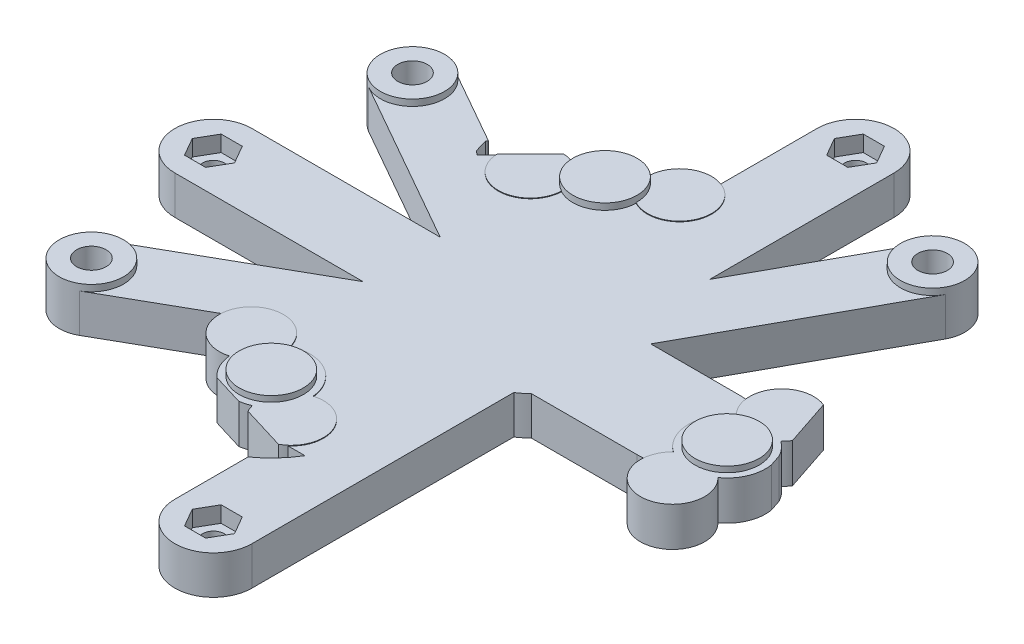
SolidWorks part; units mm, degrees
other "Fixed Star Plate"
ref_plane "Front Plane" through (0, 0, 0) normal (0, 0, 1) x (1, 0, 0)
ref_plane "Top Plane" through (0, 0, 0) normal (0, 1, 0) x (1, 0, 0)
ref_plane "Right Plane" through (0, 0, 0) normal (1, 0, 0) x (0, 0, -1)
sketch3d "Base Outline Sketch datum points"
  point P0 (0, -71, 0)
  point P1 (10, -71, 0)
  point P2 (0, -71, -10)
ref_plane "Base Outline Sketch plane" through (0, -71, 0) normal (0, 1, 0) x (1, 0, 0)
sketch "Base Outline Sketch" plane through (0, -71, 0) normal (0, 1, 0) x (1, 0, 0)
  line L0 (-32.2917, 8) -> (-46.1853, 8)
  line L1 (-24.4227, 13.1376) -> (-22.0154, 5.909)
  line L2 (-20.9711, 2.7735) -> (-20.3706, 0.9703)
  line L3 (-48.7418, -8) -> (-32.2917, -8)
  line L4 (-50.2917, -50) -> (-50.2917, -9.2195)
  line L5 (-62.2917, -38.6002) -> (-62.2917, -50)
  line L6 (-58.0273, -34) -> (-60.6452, -34)
  line L7 (-61.5389, -34.6217) -> (-68.3642, -32.542)
  line L8 (-70.4166, -31.9166) -> (-75.3281, -30.42)
  line L9 (-97.8216, -29.3473) -> (-83.633, -21.2856)
  line L10 (-76.9729, -6) -> (-102.7617, -20.6527)
  line L11 (-106.2917, -6) -> (-76.9729, -6)
  line L12 (-76.9729, 6) -> (-106.2917, 6)
  line L13 (-102.7617, 20.6527) -> (-76.9729, 6)
  line L14 (-86.2562, 22.776) -> (-97.8216, 29.3473)
  line L15 (-86.2562, 22.776) -> (-86.3054, 22.6772)
  line L16 (-86.3054, 22.6772) -> (-86.3838, 22.4486)
  line L17 (-85.7572, 20.4132) -> (-85.2034, 19.9887)
  line L18 (-85.2034, 19.9887) -> (-83.8108, 21.3866)
  line L19 (-83.633, 21.2856) -> (-83.8108, 21.3866)
  line L20 (-83.6495, 21.5484) -> (-78.4893, 26.7281)
  line L21 (-62.2917, 50) -> (-62.2917, 34.9546)
  line L22 (-50.2917, 21.2843) -> (-50.2917, 50)
  line L23 (-38.6727, 42.4096) -> (-50.2917, 21.2843)
  line L24 (-46.1853, 8) -> (-29.9106, 37.5904)
  circle A0 centre (-71.2917, -25.9808) radius 3.95
  circle A1 centre (-63.9304, -30.2308) radius 1.75
  circle A2 centre (-26.2917, 0) radius 3.95
  circle A3 centre (-56.2917, -50) radius 3.1
  circle A4 centre (-26.2917, -8.5) radius 1.75
  circle A5 centre (-78.6529, -21.7308) radius 1.75
  circle A6 centre (-100.2917, -25) radius 2.3
  circle A7 centre (-71.2917, 25.9808) radius 3.95
  circle A8 centre (-34.2917, 40) radius 2.3
  circle A9 centre (-26.2917, 8.5) radius 1.75
  circle A10 centre (-63.9304, 30.2308) radius 1.75
  circle A11 centre (-56.2917, 50) radius 3.1
  circle A12 centre (-78.6529, 21.7308) radius 1.75
  circle A13 centre (-106.2917, 0) radius 3.1
  circle A14 centre (-100.2917, 25) radius 2.3
  arc A15 (-31.2594, 7.9331) -> (-32.2917, 8) centre (-32.2917, 0) ccw
  arc A16 (-24.4227, 13.1376) -> (-31.2594, 7.9331) centre (-26.2917, 8.5) ccw
  arc A17 (-22.8248, 4.8971) -> (-22.0154, 5.909) centre (-26.2917, 8.5) ccw
  arc A18 (-20.9711, 2.7735) -> (-22.8248, 4.8971) centre (-26.2917, 0) ccw
  arc A19 (-22.8248, -4.8971) -> (-20.3706, 0.9703) centre (-26.2917, 0) ccw
  arc A20 (-31.2594, -7.9331) -> (-22.8248, -4.8971) centre (-26.2917, -8.5) ccw
  arc A21 (-32.2917, -8) -> (-31.2594, -7.9331) centre (-32.2917, 0) ccw
  arc A22 (-50.2917, -9.2195) -> (-48.7418, -8) centre (-56.2917, 0) ccw
  arc A23 (-62.2917, -50) -> (-50.2917, -50) centre (-56.2917, -50) ccw
  arc A24 (-62.2917, -38.6002) -> (-58.0273, -34) centre (-71.2917, -25.9808) ccw
  arc A25 (-61.5389, -34.6217) -> (-60.6452, -34) centre (-63.9304, -30.2308) ccw
  arc A26 (-68.7841, -31.4316) -> (-68.3642, -32.542) centre (-63.9304, -30.2308) ccw
  arc A27 (-70.4166, -31.9166) -> (-68.7841, -31.4316) centre (-71.2917, -25.9808) ccw
  arc A28 (-77.266, -26.5346) -> (-75.3281, -30.42) centre (-71.2917, -25.9808) ccw
  arc A29 (-83.633, -21.2856) -> (-77.266, -26.5346) centre (-78.6529, -21.7308) ccw
  arc A30 (-100.2917, -30) -> (-97.8216, -29.3473) centre (-100.2917, -25) ccw
  arc A31 (-102.7617, -20.6527) -> (-100.2917, -30) centre (-100.2917, -25) ccw
  arc A32 (-106.2917, 6) -> (-106.2917, -6) centre (-106.2917, 0) ccw
  arc A33 (-97.8216, 29.3473) -> (-102.7617, 20.6527) centre (-100.2917, 25) ccw
  arc A34 (-86.3838, 22.4486) -> (-85.7572, 20.4132) centre (-71.2917, 25.9808) ccw
  arc A35 (-83.6495, 21.5484) -> (-83.633, 21.2856) centre (-78.6529, 21.7308) ccw
  arc A36 (-76.2892, 26.1368) -> (-78.4893, 26.7281) centre (-78.6529, 21.7308) ccw
  arc A37 (-68.928, 30.3868) -> (-76.2892, 26.1368) centre (-71.2917, 25.9808) ccw
  arc A38 (-68.7841, 31.4316) -> (-68.928, 30.3868) centre (-63.9304, 30.2308) ccw
  arc A39 (-62.2917, 34.9546) -> (-68.7841, 31.4316) centre (-63.9304, 30.2308) ccw
  arc A40 (-50.2917, 50) -> (-62.2917, 50) centre (-56.2917, 50) ccw
  arc A41 (-29.9106, 37.5904) -> (-38.6727, 42.4096) centre (-34.2917, 40) ccw
extrude "Base Outline" add sketch "Base Outline Sketch" along normal blind 1.4 separate body
sketch3d "Interface Profile 2 Sketch datum points"
  point P0 (0, -69.6, 0)
  point P1 (10, -69.6, 0)
  point P2 (0, -69.6, -10)
ref_plane "Interface Profile 2 Sketch plane" through (0, -69.6, 0) normal (0, 1, 0) x (1, 0, 0)
sketch "Interface Profile 2 Sketch" plane through (0, -69.6, 0) normal (0, 1, 0) x (1, 0, 0)
  line L0 (-32.2917, 8) -> (-46.1853, 8)
  line L1 (-24.4227, 13.1376) -> (-22.0154, 5.909)
  line L2 (-20.9711, 2.7735) -> (-20.3706, 0.9703)
  line L3 (-48.7418, -8) -> (-32.2917, -8)
  line L4 (-50.2917, -50) -> (-50.2917, -9.2195)
  line L5 (-62.2917, -38.6002) -> (-62.2917, -50)
  line L6 (-58.0273, -34) -> (-60.6452, -34)
  line L7 (-61.5389, -34.6217) -> (-68.3642, -32.542)
  line L8 (-70.4166, -31.9166) -> (-75.3281, -30.42)
  line L9 (-97.8216, -29.3473) -> (-83.633, -21.2856)
  line L10 (-76.9729, -6) -> (-102.7617, -20.6527)
  line L11 (-106.2917, -6) -> (-76.9729, -6)
  line L12 (-76.9729, 6) -> (-106.2917, 6)
  line L13 (-102.7617, 20.6527) -> (-76.9729, 6)
  line L14 (-86.2562, 22.776) -> (-97.8216, 29.3473)
  line L15 (-86.2562, 22.776) -> (-86.3054, 22.6772)
  line L16 (-86.3054, 22.6772) -> (-86.3838, 22.4486)
  line L17 (-85.7572, 20.4132) -> (-85.2034, 19.9887)
  line L18 (-85.2034, 19.9887) -> (-83.8108, 21.3866)
  line L19 (-83.633, 21.2856) -> (-83.8108, 21.3866)
  line L20 (-83.6495, 21.5484) -> (-78.4893, 26.7281)
  line L21 (-62.2917, 50) -> (-62.2917, 34.9546)
  line L22 (-50.2917, 21.2843) -> (-50.2917, 50)
  line L23 (-38.6727, 42.4096) -> (-50.2917, 21.2843)
  line L24 (-46.1853, 8) -> (-29.9106, 37.5904)
  circle A0 centre (-71.2917, -25.9808) radius 3.95
  circle A1 centre (-63.9304, -30.2308) radius 1.75
  circle A2 centre (-26.2917, 0) radius 3.95
  circle A3 centre (-56.2917, -50) radius 1.7
  circle A4 centre (-56.2917, 50) radius 1.7
  circle A5 centre (-106.2917, 0) radius 1.7
  circle A6 centre (-26.2917, -8.5) radius 1.75
  circle A7 centre (-78.6529, -21.7308) radius 1.75
  circle A8 centre (-100.2917, -25) radius 2.3
  circle A9 centre (-71.2917, 25.9808) radius 3.95
  circle A10 centre (-34.2917, 40) radius 2.3
  circle A11 centre (-26.2917, 8.5) radius 1.75
  circle A12 centre (-63.9304, 30.2308) radius 1.75
  circle A13 centre (-78.6529, 21.7308) radius 1.75
  circle A14 centre (-100.2917, 25) radius 2.3
  arc A15 (-31.2594, 7.9331) -> (-32.2917, 8) centre (-32.2917, 0) ccw
  arc A16 (-24.4227, 13.1376) -> (-31.2594, 7.9331) centre (-26.2917, 8.5) ccw
  arc A17 (-22.8248, 4.8971) -> (-22.0154, 5.909) centre (-26.2917, 8.5) ccw
  arc A18 (-20.9711, 2.7735) -> (-22.8248, 4.8971) centre (-26.2917, 0) ccw
  arc A19 (-22.8248, -4.8971) -> (-20.3706, 0.9703) centre (-26.2917, 0) ccw
  arc A20 (-31.2594, -7.9331) -> (-22.8248, -4.8971) centre (-26.2917, -8.5) ccw
  arc A21 (-32.2917, -8) -> (-31.2594, -7.9331) centre (-32.2917, 0) ccw
  arc A22 (-50.2917, -9.2195) -> (-48.7418, -8) centre (-56.2917, 0) ccw
  arc A23 (-62.2917, -50) -> (-50.2917, -50) centre (-56.2917, -50) ccw
  arc A24 (-62.2917, -38.6002) -> (-58.0273, -34) centre (-71.2917, -25.9808) ccw
  arc A25 (-61.5389, -34.6217) -> (-60.6452, -34) centre (-63.9304, -30.2308) ccw
  arc A26 (-68.7841, -31.4316) -> (-68.3642, -32.542) centre (-63.9304, -30.2308) ccw
  arc A27 (-70.4166, -31.9166) -> (-68.7841, -31.4316) centre (-71.2917, -25.9808) ccw
  arc A28 (-77.266, -26.5346) -> (-75.3281, -30.42) centre (-71.2917, -25.9808) ccw
  arc A29 (-83.633, -21.2856) -> (-77.266, -26.5346) centre (-78.6529, -21.7308) ccw
  arc A30 (-100.2917, -30) -> (-97.8216, -29.3473) centre (-100.2917, -25) ccw
  arc A31 (-102.7617, -20.6527) -> (-100.2917, -30) centre (-100.2917, -25) ccw
  arc A32 (-106.2917, 6) -> (-106.2917, -6) centre (-106.2917, 0) ccw
  arc A33 (-97.8216, 29.3473) -> (-102.7617, 20.6527) centre (-100.2917, 25) ccw
  arc A34 (-86.3838, 22.4486) -> (-85.7572, 20.4132) centre (-71.2917, 25.9808) ccw
  arc A35 (-83.6495, 21.5484) -> (-83.633, 21.2856) centre (-78.6529, 21.7308) ccw
  arc A36 (-76.2892, 26.1368) -> (-78.4893, 26.7281) centre (-78.6529, 21.7308) ccw
  arc A37 (-68.928, 30.3868) -> (-76.2892, 26.1368) centre (-71.2917, 25.9808) ccw
  arc A38 (-68.7841, 31.4316) -> (-68.928, 30.3868) centre (-63.9304, 30.2308) ccw
  arc A39 (-62.2917, 34.9546) -> (-68.7841, 31.4316) centre (-63.9304, 30.2308) ccw
  arc A40 (-50.2917, 50) -> (-62.2917, 50) centre (-56.2917, 50) ccw
  arc A41 (-29.9106, 37.5904) -> (-38.6727, 42.4096) centre (-34.2917, 40) ccw
extrude "Interface Profile 2" add sketch "Interface Profile 2 Sketch" along normal blind 0.1
sketch3d "Interface Profile 3 Sketch datum points"
  point P0 (0, -69.5, 0)
  point P1 (10, -69.5, 0)
  point P2 (0, -69.5, -10)
ref_plane "Interface Profile 3 Sketch plane" through (0, -69.5, 0) normal (0, 1, 0) x (1, 0, 0)
sketch "Interface Profile 3 Sketch" plane through (0, -69.5, 0) normal (0, 1, 0) x (1, 0, 0)
  line L0 (-70.8027, -29.9004) -> (-74.9306, -27.5171)
  line L1 (-23.1417, 2.3833) -> (-23.1417, -2.3833)
  line L2 (-74.9306, 27.5171) -> (-70.8027, 29.9004)
  line L3 (-32.2917, 8) -> (-46.1853, 8)
  line L4 (-24.4227, 13.1376) -> (-22.0154, 5.909)
  line L5 (-20.9711, 2.7735) -> (-20.3706, 0.9703)
  line L6 (-48.7418, -8) -> (-32.2917, -8)
  line L7 (-50.2917, -50) -> (-50.2917, -9.2195)
  line L8 (-62.2917, -38.6002) -> (-62.2917, -50)
  line L9 (-58.0273, -34) -> (-60.6452, -34)
  line L10 (-61.5389, -34.6217) -> (-68.3642, -32.542)
  line L11 (-70.4166, -31.9166) -> (-75.3281, -30.42)
  line L12 (-97.8216, -29.3473) -> (-83.633, -21.2856)
  line L13 (-76.9729, -6) -> (-102.7617, -20.6527)
  line L14 (-106.2917, -6) -> (-76.9729, -6)
  line L15 (-76.9729, 6) -> (-106.2917, 6)
  line L16 (-102.7617, 20.6527) -> (-76.9729, 6)
  line L17 (-86.2562, 22.776) -> (-97.8216, 29.3473)
  line L18 (-86.2562, 22.776) -> (-86.3054, 22.6772)
  line L19 (-86.3054, 22.6772) -> (-86.3838, 22.4486)
  line L20 (-85.7572, 20.4132) -> (-85.2034, 19.9887)
  line L21 (-85.2034, 19.9887) -> (-83.8108, 21.3866)
  line L22 (-83.633, 21.2856) -> (-83.8108, 21.3866)
  line L23 (-83.6495, 21.5484) -> (-78.4893, 26.7281)
  line L24 (-62.2917, 50) -> (-62.2917, 34.9546)
  line L25 (-50.2917, 21.2843) -> (-50.2917, 50)
  line L26 (-38.6727, 42.4096) -> (-50.2917, 21.2843)
  line L27 (-46.1853, 8) -> (-29.9106, 37.5904)
  arc A0 (-67.3417, -25.9808) -> (-70.8027, -29.9004) centre (-71.2917, -25.9808) cw
  arc A1 (-74.9306, -27.5171) -> (-67.3417, -25.9808) centre (-71.2917, -25.9808) cw
  circle A2 centre (-63.9304, -30.2308) radius 1.75
  arc A3 (-23.1417, -2.3833) -> (-23.1417, 2.3833) centre (-26.2917, 0) cw
  circle A4 centre (-56.2917, -50) radius 1.7
  circle A5 centre (-56.2917, 50) radius 1.7
  circle A6 centre (-106.2917, 0) radius 1.7
  circle A7 centre (-26.2917, -8.5) radius 1.75
  circle A8 centre (-78.6529, -21.7308) radius 1.75
  circle A9 centre (-100.2917, -25) radius 2.3
  arc A10 (-67.3417, 25.9808) -> (-74.9306, 27.5171) centre (-71.2917, 25.9808) cw
  arc A11 (-70.8027, 29.9004) -> (-67.3417, 25.9808) centre (-71.2917, 25.9808) cw
  circle A12 centre (-34.2917, 40) radius 2.3
  circle A13 centre (-26.2917, 8.5) radius 1.75
  circle A14 centre (-63.9304, 30.2308) radius 1.75
  circle A15 centre (-78.6529, 21.7308) radius 1.75
  circle A16 centre (-100.2917, 25) radius 2.3
  arc A17 (-31.2594, 7.9331) -> (-32.2917, 8) centre (-32.2917, 0) ccw
  arc A18 (-24.4227, 13.1376) -> (-31.2594, 7.9331) centre (-26.2917, 8.5) ccw
  arc A19 (-22.8248, 4.8971) -> (-22.0154, 5.909) centre (-26.2917, 8.5) ccw
  arc A20 (-20.9711, 2.7735) -> (-22.8248, 4.8971) centre (-26.2917, 0) ccw
  arc A21 (-22.8248, -4.8971) -> (-20.3706, 0.9703) centre (-26.2917, 0) ccw
  arc A22 (-31.2594, -7.9331) -> (-22.8248, -4.8971) centre (-26.2917, -8.5) ccw
  arc A23 (-32.2917, -8) -> (-31.2594, -7.9331) centre (-32.2917, 0) ccw
  arc A24 (-50.2917, -9.2195) -> (-48.7418, -8) centre (-56.2917, 0) ccw
  arc A25 (-62.2917, -50) -> (-50.2917, -50) centre (-56.2917, -50) ccw
  arc A26 (-62.2917, -38.6002) -> (-58.0273, -34) centre (-71.2917, -25.9808) ccw
  arc A27 (-61.5389, -34.6217) -> (-60.6452, -34) centre (-63.9304, -30.2308) ccw
  arc A28 (-68.7841, -31.4316) -> (-68.3642, -32.542) centre (-63.9304, -30.2308) ccw
  arc A29 (-70.4166, -31.9166) -> (-68.7841, -31.4316) centre (-71.2917, -25.9808) ccw
  arc A30 (-77.266, -26.5346) -> (-75.3281, -30.42) centre (-71.2917, -25.9808) ccw
  arc A31 (-83.633, -21.2856) -> (-77.266, -26.5346) centre (-78.6529, -21.7308) ccw
  arc A32 (-100.2917, -30) -> (-97.8216, -29.3473) centre (-100.2917, -25) ccw
  arc A33 (-102.7617, -20.6527) -> (-100.2917, -30) centre (-100.2917, -25) ccw
  arc A34 (-106.2917, 6) -> (-106.2917, -6) centre (-106.2917, 0) ccw
  arc A35 (-97.8216, 29.3473) -> (-102.7617, 20.6527) centre (-100.2917, 25) ccw
  arc A36 (-86.3838, 22.4486) -> (-85.7572, 20.4132) centre (-71.2917, 25.9808) ccw
  arc A37 (-83.6495, 21.5484) -> (-83.633, 21.2856) centre (-78.6529, 21.7308) ccw
  arc A38 (-76.2892, 26.1368) -> (-78.4893, 26.7281) centre (-78.6529, 21.7308) ccw
  arc A39 (-68.928, 30.3868) -> (-76.2892, 26.1368) centre (-71.2917, 25.9808) ccw
  arc A40 (-68.7841, 31.4316) -> (-68.928, 30.3868) centre (-63.9304, 30.2308) ccw
  arc A41 (-62.2917, 34.9546) -> (-68.7841, 31.4316) centre (-63.9304, 30.2308) ccw
  arc A42 (-50.2917, 50) -> (-62.2917, 50) centre (-56.2917, 50) ccw
  arc A43 (-29.9106, 37.5904) -> (-38.6727, 42.4096) centre (-34.2917, 40) ccw
extrude "Interface Profile 3" add sketch "Interface Profile 3 Sketch" along normal blind 0.5
sketch3d "Interface Profile 4 Sketch datum points"
  point P0 (0, -69, 0)
  point P1 (10, -69, 0)
  point P2 (0, -69, -10)
ref_plane "Interface Profile 4 Sketch plane" through (0, -69, 0) normal (0, 1, 0) x (1, 0, 0)
sketch "Interface Profile 4 Sketch" plane through (0, -69, 0) normal (0, 1, 0) x (1, 0, 0)
  line L0 (-32.2917, 8) -> (-46.1853, 8)
  line L1 (-24.4227, 13.1376) -> (-22.0154, 5.909)
  line L2 (-20.9711, 2.7735) -> (-20.3706, 0.9703)
  line L3 (-48.7418, -8) -> (-32.2917, -8)
  line L4 (-50.2917, -50) -> (-50.2917, -9.2195)
  line L5 (-62.2917, -38.6002) -> (-62.2917, -50)
  line L6 (-58.0273, -34) -> (-60.6452, -34)
  line L7 (-61.5389, -34.6217) -> (-68.3642, -32.542)
  line L8 (-70.4166, -31.9166) -> (-75.3281, -30.42)
  line L9 (-97.8216, -29.3473) -> (-83.633, -21.2856)
  line L10 (-76.9729, -6) -> (-102.7617, -20.6527)
  line L11 (-106.2917, -6) -> (-76.9729, -6)
  line L12 (-76.9729, 6) -> (-106.2917, 6)
  line L13 (-102.7617, 20.6527) -> (-76.9729, 6)
  line L14 (-86.2562, 22.776) -> (-97.8216, 29.3473)
  line L15 (-86.2562, 22.776) -> (-86.3054, 22.6772)
  line L16 (-86.3054, 22.6772) -> (-86.3838, 22.4486)
  line L17 (-85.7572, 20.4132) -> (-85.2034, 19.9887)
  line L18 (-85.2034, 19.9887) -> (-83.8108, 21.3866)
  line L19 (-83.633, 21.2856) -> (-83.8108, 21.3866)
  line L20 (-83.6495, 21.5484) -> (-78.4893, 26.7281)
  line L21 (-62.2917, 50) -> (-62.2917, 34.9546)
  line L22 (-50.2917, 21.2843) -> (-50.2917, 50)
  line L23 (-38.6727, 42.4096) -> (-50.2917, 21.2843)
  line L24 (-46.1853, 8) -> (-29.9106, 37.5904)
  circle A0 centre (-63.9304, -30.2308) radius 1.75
  circle A1 centre (-56.2917, -50) radius 1.7
  circle A2 centre (-56.2917, 50) radius 1.7
  circle A3 centre (-106.2917, 0) radius 1.7
  circle A4 centre (-26.2917, -8.5) radius 1.75
  circle A5 centre (-78.6529, -21.7308) radius 1.75
  circle A6 centre (-100.2917, -25) radius 2.3
  circle A7 centre (-34.2917, 40) radius 2.3
  circle A8 centre (-26.2917, 8.5) radius 1.75
  circle A9 centre (-63.9304, 30.2308) radius 1.75
  circle A10 centre (-78.6529, 21.7308) radius 1.75
  circle A11 centre (-100.2917, 25) radius 2.3
  arc A12 (-31.2594, 7.9331) -> (-32.2917, 8) centre (-32.2917, 0) ccw
  arc A13 (-24.4227, 13.1376) -> (-31.2594, 7.9331) centre (-26.2917, 8.5) ccw
  arc A14 (-22.8248, 4.8971) -> (-22.0154, 5.909) centre (-26.2917, 8.5) ccw
  arc A15 (-20.9711, 2.7735) -> (-22.8248, 4.8971) centre (-26.2917, 0) ccw
  arc A16 (-22.8248, -4.8971) -> (-20.3706, 0.9703) centre (-26.2917, 0) ccw
  arc A17 (-31.2594, -7.9331) -> (-22.8248, -4.8971) centre (-26.2917, -8.5) ccw
  arc A18 (-32.2917, -8) -> (-31.2594, -7.9331) centre (-32.2917, 0) ccw
  arc A19 (-50.2917, -9.2195) -> (-48.7418, -8) centre (-56.2917, 0) ccw
  arc A20 (-62.2917, -50) -> (-50.2917, -50) centre (-56.2917, -50) ccw
  arc A21 (-62.2917, -38.6002) -> (-58.0273, -34) centre (-71.2917, -25.9808) ccw
  arc A22 (-61.5389, -34.6217) -> (-60.6452, -34) centre (-63.9304, -30.2308) ccw
  arc A23 (-68.7841, -31.4316) -> (-68.3642, -32.542) centre (-63.9304, -30.2308) ccw
  arc A24 (-70.4166, -31.9166) -> (-68.7841, -31.4316) centre (-71.2917, -25.9808) ccw
  arc A25 (-77.266, -26.5346) -> (-75.3281, -30.42) centre (-71.2917, -25.9808) ccw
  arc A26 (-83.633, -21.2856) -> (-77.266, -26.5346) centre (-78.6529, -21.7308) ccw
  arc A27 (-100.2917, -30) -> (-97.8216, -29.3473) centre (-100.2917, -25) ccw
  arc A28 (-102.7617, -20.6527) -> (-100.2917, -30) centre (-100.2917, -25) ccw
  arc A29 (-106.2917, 6) -> (-106.2917, -6) centre (-106.2917, 0) ccw
  arc A30 (-97.8216, 29.3473) -> (-102.7617, 20.6527) centre (-100.2917, 25) ccw
  arc A31 (-86.3838, 22.4486) -> (-85.7572, 20.4132) centre (-71.2917, 25.9808) ccw
  arc A32 (-83.6495, 21.5484) -> (-83.633, 21.2856) centre (-78.6529, 21.7308) ccw
  arc A33 (-76.2892, 26.1368) -> (-78.4893, 26.7281) centre (-78.6529, 21.7308) ccw
  arc A34 (-68.928, 30.3868) -> (-76.2892, 26.1368) centre (-71.2917, 25.9808) ccw
  arc A35 (-68.7841, 31.4316) -> (-68.928, 30.3868) centre (-63.9304, 30.2308) ccw
  arc A36 (-62.2917, 34.9546) -> (-68.7841, 31.4316) centre (-63.9304, 30.2308) ccw
  arc A37 (-50.2917, 50) -> (-62.2917, 50) centre (-56.2917, 50) ccw
  arc A38 (-29.9106, 37.5904) -> (-38.6727, 42.4096) centre (-34.2917, 40) ccw
extrude "Interface Profile 4" add sketch "Interface Profile 4 Sketch" along normal blind 1.5
sketch3d "Interface Profile 5 Sketch datum points"
  point P0 (0, -67.5, 0)
  point P1 (10, -67.5, 0)
  point P2 (0, -67.5, -10)
ref_plane "Interface Profile 5 Sketch plane" through (0, -67.5, 0) normal (0, 1, 0) x (1, 0, 0)
sketch "Interface Profile 5 Sketch" plane through (0, -67.5, 0) normal (0, 1, 0) x (1, 0, 0)
  line L0 (-59.5825, -50) -> (-57.9371, -47.15)
  line L1 (-57.9371, -52.85) -> (-59.5825, -50)
  line L2 (-57.9371, -47.15) -> (-54.6462, -47.15)
  line L3 (-54.6462, 52.85) -> (-53.0008, 50)
  line L4 (-57.9371, 52.85) -> (-54.6462, 52.85)
  line L5 (-53.0008, 50) -> (-54.6462, 47.15)
  line L6 (-59.5825, 50) -> (-57.9371, 52.85)
  line L7 (-57.9371, 47.15) -> (-59.5825, 50)
  line L8 (-54.6462, 47.15) -> (-57.9371, 47.15)
  line L9 (-104.6462, 2.85) -> (-103.0008, 0)
  line L10 (-107.9371, 2.85) -> (-104.6462, 2.85)
  line L11 (-103.0008, 0) -> (-104.6462, -2.85)
  line L12 (-109.5825, 0) -> (-107.9371, 2.85)
  line L13 (-107.9371, -2.85) -> (-109.5825, 0)
  line L14 (-104.6462, -2.85) -> (-107.9371, -2.85)
  line L15 (-54.6462, -52.85) -> (-57.9371, -52.85)
  line L16 (-54.6462, -47.15) -> (-53.0008, -50)
  line L17 (-53.0008, -50) -> (-54.6462, -52.85)
  line L18 (-32.2917, 8) -> (-46.1853, 8)
  line L19 (-24.4227, 13.1376) -> (-22.0154, 5.909)
  line L20 (-20.9711, 2.7735) -> (-20.3706, 0.9703)
  line L21 (-48.7418, -8) -> (-32.2917, -8)
  line L22 (-50.2917, -50) -> (-50.2917, -9.2195)
  line L23 (-62.2917, -38.6002) -> (-62.2917, -50)
  line L24 (-58.0273, -34) -> (-60.6452, -34)
  line L25 (-61.5389, -34.6217) -> (-68.3642, -32.542)
  line L26 (-70.4166, -31.9166) -> (-75.3281, -30.42)
  line L27 (-97.8216, -29.3473) -> (-83.633, -21.2856)
  line L28 (-76.9729, -6) -> (-102.7617, -20.6527)
  line L29 (-106.2917, -6) -> (-76.9729, -6)
  line L30 (-76.9729, 6) -> (-106.2917, 6)
  line L31 (-102.7617, 20.6527) -> (-76.9729, 6)
  line L32 (-86.2562, 22.776) -> (-97.8216, 29.3473)
  line L33 (-86.2562, 22.776) -> (-86.3054, 22.6772)
  line L34 (-86.3054, 22.6772) -> (-86.3838, 22.4486)
  line L35 (-85.7572, 20.4132) -> (-85.2034, 19.9887)
  line L36 (-85.2034, 19.9887) -> (-83.8108, 21.3866)
  line L37 (-83.633, 21.2856) -> (-83.8108, 21.3866)
  line L38 (-83.6495, 21.5484) -> (-78.4893, 26.7281)
  line L39 (-62.2917, 50) -> (-62.2917, 34.9546)
  line L40 (-50.2917, 21.2843) -> (-50.2917, 50)
  line L41 (-38.6727, 42.4096) -> (-50.2917, 21.2843)
  line L42 (-46.1853, 8) -> (-29.9106, 37.5904)
  circle A0 centre (-63.9304, -30.2308) radius 1.75
  circle A1 centre (-26.2917, -8.5) radius 1.75
  circle A2 centre (-78.6529, -21.7308) radius 1.75
  circle A3 centre (-100.2917, -25) radius 2.3
  circle A4 centre (-34.2917, 40) radius 2.3
  circle A5 centre (-26.2917, 8.5) radius 1.75
  circle A6 centre (-63.9304, 30.2308) radius 1.75
  circle A7 centre (-78.6529, 21.7308) radius 1.75
  circle A8 centre (-100.2917, 25) radius 2.3
  arc A9 (-31.2594, 7.9331) -> (-32.2917, 8) centre (-32.2917, 0) ccw
  arc A10 (-24.4227, 13.1376) -> (-31.2594, 7.9331) centre (-26.2917, 8.5) ccw
  arc A11 (-22.8248, 4.8971) -> (-22.0154, 5.909) centre (-26.2917, 8.5) ccw
  arc A12 (-20.9711, 2.7735) -> (-22.8248, 4.8971) centre (-26.2917, 0) ccw
  arc A13 (-22.8248, -4.8971) -> (-20.3706, 0.9703) centre (-26.2917, 0) ccw
  arc A14 (-31.2594, -7.9331) -> (-22.8248, -4.8971) centre (-26.2917, -8.5) ccw
  arc A15 (-32.2917, -8) -> (-31.2594, -7.9331) centre (-32.2917, 0) ccw
  arc A16 (-50.2917, -9.2195) -> (-48.7418, -8) centre (-56.2917, 0) ccw
  arc A17 (-62.2917, -50) -> (-50.2917, -50) centre (-56.2917, -50) ccw
  arc A18 (-62.2917, -38.6002) -> (-58.0273, -34) centre (-71.2917, -25.9808) ccw
  arc A19 (-61.5389, -34.6217) -> (-60.6452, -34) centre (-63.9304, -30.2308) ccw
  arc A20 (-68.7841, -31.4316) -> (-68.3642, -32.542) centre (-63.9304, -30.2308) ccw
  arc A21 (-70.4166, -31.9166) -> (-68.7841, -31.4316) centre (-71.2917, -25.9808) ccw
  arc A22 (-77.266, -26.5346) -> (-75.3281, -30.42) centre (-71.2917, -25.9808) ccw
  arc A23 (-83.633, -21.2856) -> (-77.266, -26.5346) centre (-78.6529, -21.7308) ccw
  arc A24 (-100.2917, -30) -> (-97.8216, -29.3473) centre (-100.2917, -25) ccw
  arc A25 (-102.7617, -20.6527) -> (-100.2917, -30) centre (-100.2917, -25) ccw
  arc A26 (-106.2917, 6) -> (-106.2917, -6) centre (-106.2917, 0) ccw
  arc A27 (-97.8216, 29.3473) -> (-102.7617, 20.6527) centre (-100.2917, 25) ccw
  arc A28 (-86.3838, 22.4486) -> (-85.7572, 20.4132) centre (-71.2917, 25.9808) ccw
  arc A29 (-83.6495, 21.5484) -> (-83.633, 21.2856) centre (-78.6529, 21.7308) ccw
  arc A30 (-76.2892, 26.1368) -> (-78.4893, 26.7281) centre (-78.6529, 21.7308) ccw
  arc A31 (-68.928, 30.3868) -> (-76.2892, 26.1368) centre (-71.2917, 25.9808) ccw
  arc A32 (-68.7841, 31.4316) -> (-68.928, 30.3868) centre (-63.9304, 30.2308) ccw
  arc A33 (-62.2917, 34.9546) -> (-68.7841, 31.4316) centre (-63.9304, 30.2308) ccw
  arc A34 (-50.2917, 50) -> (-62.2917, 50) centre (-56.2917, 50) ccw
  arc A35 (-29.9106, 37.5904) -> (-38.6727, 42.4096) centre (-34.2917, 40) ccw
extrude "Interface Profile 5" add sketch "Interface Profile 5 Sketch" along normal blind 0.5
sketch3d "Interface Profile 6 Sketch datum points"
  point P0 (0, -67, 0)
  point P1 (10, -67, 0)
  point P2 (0, -67, -10)
ref_plane "Interface Profile 6 Sketch plane" through (0, -67, 0) normal (0, 1, 0) x (1, 0, 0)
sketch "Interface Profile 6 Sketch" plane through (0, -67, 0) normal (0, 1, 0) x (1, 0, 0)
  line L0 (-59.5825, -50) -> (-57.9371, -47.15)
  line L1 (-57.9371, -52.85) -> (-59.5825, -50)
  line L2 (-57.9371, -47.15) -> (-54.6462, -47.15)
  line L3 (-54.6462, 52.85) -> (-53.0008, 50)
  line L4 (-57.9371, 52.85) -> (-54.6462, 52.85)
  line L5 (-53.0008, 50) -> (-54.6462, 47.15)
  line L6 (-59.5825, 50) -> (-57.9371, 52.85)
  line L7 (-57.9371, 47.15) -> (-59.5825, 50)
  line L8 (-54.6462, 47.15) -> (-57.9371, 47.15)
  line L9 (-104.6462, 2.85) -> (-103.0008, 0)
  line L10 (-107.9371, 2.85) -> (-104.6462, 2.85)
  line L11 (-103.0008, 0) -> (-104.6462, -2.85)
  line L12 (-109.5825, 0) -> (-107.9371, 2.85)
  line L13 (-107.9371, -2.85) -> (-109.5825, 0)
  line L14 (-104.6462, -2.85) -> (-107.9371, -2.85)
  line L15 (-54.6462, -52.85) -> (-57.9371, -52.85)
  line L16 (-54.6462, -47.15) -> (-53.0008, -50)
  line L17 (-53.0008, -50) -> (-54.6462, -52.85)
  line L18 (-32.2917, 8) -> (-46.1853, 8)
  line L19 (-24.4227, 13.1376) -> (-22.0154, 5.909)
  line L20 (-20.9711, 2.7735) -> (-20.3706, 0.9703)
  line L21 (-48.7418, -8) -> (-32.2917, -8)
  line L22 (-50.2917, -50) -> (-50.2917, -9.2195)
  line L23 (-62.2917, -38.6002) -> (-62.2917, -50)
  line L24 (-58.0273, -34) -> (-60.6452, -34)
  line L25 (-61.5389, -34.6217) -> (-68.3642, -32.542)
  line L26 (-70.4166, -31.9166) -> (-75.3281, -30.42)
  line L27 (-97.8216, -29.3473) -> (-83.633, -21.2856)
  line L28 (-76.9729, -6) -> (-102.7617, -20.6527)
  line L29 (-106.2917, -6) -> (-76.9729, -6)
  line L30 (-76.9729, 6) -> (-106.2917, 6)
  line L31 (-102.7617, 20.6527) -> (-76.9729, 6)
  line L32 (-86.2562, 22.776) -> (-97.8216, 29.3473)
  line L33 (-86.2562, 22.776) -> (-86.3054, 22.6772)
  line L34 (-86.3054, 22.6772) -> (-86.3838, 22.4486)
  line L35 (-85.7572, 20.4132) -> (-85.2034, 19.9887)
  line L36 (-85.2034, 19.9887) -> (-83.8108, 21.3866)
  line L37 (-83.633, 21.2856) -> (-83.8108, 21.3866)
  line L38 (-83.6495, 21.5484) -> (-78.4893, 26.7281)
  line L39 (-62.2917, 50) -> (-62.2917, 34.9546)
  line L40 (-50.2917, 21.2843) -> (-50.2917, 50)
  line L41 (-38.6727, 42.4096) -> (-50.2917, 21.2843)
  line L42 (-46.1853, 8) -> (-29.9106, 37.5904)
  circle A0 centre (-63.9304, -30.2308) radius 1.1
  circle A1 centre (-26.2917, -8.5) radius 1.1
  circle A2 centre (-78.6529, -21.7308) radius 1.1
  circle A3 centre (-100.2917, -25) radius 2.3
  circle A4 centre (-34.2917, 40) radius 2.3
  circle A5 centre (-26.2917, 8.5) radius 1.1
  circle A6 centre (-63.9304, 30.2308) radius 1.1
  circle A7 centre (-78.6529, 21.7308) radius 1.1
  circle A8 centre (-100.2917, 25) radius 2.3
  arc A9 (-31.2594, 7.9331) -> (-32.2917, 8) centre (-32.2917, 0) ccw
  arc A10 (-24.4227, 13.1376) -> (-31.2594, 7.9331) centre (-26.2917, 8.5) ccw
  arc A11 (-22.8248, 4.8971) -> (-22.0154, 5.909) centre (-26.2917, 8.5) ccw
  arc A12 (-20.9711, 2.7735) -> (-22.8248, 4.8971) centre (-26.2917, 0) ccw
  arc A13 (-22.8248, -4.8971) -> (-20.3706, 0.9703) centre (-26.2917, 0) ccw
  arc A14 (-31.2594, -7.9331) -> (-22.8248, -4.8971) centre (-26.2917, -8.5) ccw
  arc A15 (-32.2917, -8) -> (-31.2594, -7.9331) centre (-32.2917, 0) ccw
  arc A16 (-50.2917, -9.2195) -> (-48.7418, -8) centre (-56.2917, 0) ccw
  arc A17 (-62.2917, -50) -> (-50.2917, -50) centre (-56.2917, -50) ccw
  arc A18 (-62.2917, -38.6002) -> (-58.0273, -34) centre (-71.2917, -25.9808) ccw
  arc A19 (-61.5389, -34.6217) -> (-60.6452, -34) centre (-63.9304, -30.2308) ccw
  arc A20 (-68.7841, -31.4316) -> (-68.3642, -32.542) centre (-63.9304, -30.2308) ccw
  arc A21 (-70.4166, -31.9166) -> (-68.7841, -31.4316) centre (-71.2917, -25.9808) ccw
  arc A22 (-77.266, -26.5346) -> (-75.3281, -30.42) centre (-71.2917, -25.9808) ccw
  arc A23 (-83.633, -21.2856) -> (-77.266, -26.5346) centre (-78.6529, -21.7308) ccw
  arc A24 (-100.2917, -30) -> (-97.8216, -29.3473) centre (-100.2917, -25) ccw
  arc A25 (-102.7617, -20.6527) -> (-100.2917, -30) centre (-100.2917, -25) ccw
  arc A26 (-106.2917, 6) -> (-106.2917, -6) centre (-106.2917, 0) ccw
  arc A27 (-97.8216, 29.3473) -> (-102.7617, 20.6527) centre (-100.2917, 25) ccw
  arc A28 (-86.3838, 22.4486) -> (-85.7572, 20.4132) centre (-71.2917, 25.9808) ccw
  arc A29 (-83.6495, 21.5484) -> (-83.633, 21.2856) centre (-78.6529, 21.7308) ccw
  arc A30 (-76.2892, 26.1368) -> (-78.4893, 26.7281) centre (-78.6529, 21.7308) ccw
  arc A31 (-68.928, 30.3868) -> (-76.2892, 26.1368) centre (-71.2917, 25.9808) ccw
  arc A32 (-68.7841, 31.4316) -> (-68.928, 30.3868) centre (-63.9304, 30.2308) ccw
  arc A33 (-62.2917, 34.9546) -> (-68.7841, 31.4316) centre (-63.9304, 30.2308) ccw
  arc A34 (-50.2917, 50) -> (-62.2917, 50) centre (-56.2917, 50) ccw
  arc A35 (-29.9106, 37.5904) -> (-38.6727, 42.4096) centre (-34.2917, 40) ccw
extrude "Interface Profile 6" add sketch "Interface Profile 6 Sketch" along normal blind 1.3
sketch3d "Interface Profile 7 Sketch datum points"
  point P0 (0, -65.7, 0)
  point P1 (10, -65.7, 0)
  point P2 (0, -65.7, -10)
ref_plane "Interface Profile 7 Sketch plane" through (0, -65.7, 0) normal (0, 1, 0) x (1, 0, 0)
sketch "Interface Profile 7 Sketch" plane through (0, -65.7, 0) normal (0, 1, 0) x (1, 0, 0)
  line L0 (-59.5825, -50) -> (-57.9371, -47.15)
  line L1 (-57.9371, -52.85) -> (-59.5825, -50)
  line L2 (-57.9371, -47.15) -> (-54.6462, -47.15)
  line L3 (-54.6462, 52.85) -> (-53.0008, 50)
  line L4 (-57.9371, 52.85) -> (-54.6462, 52.85)
  line L5 (-53.0008, 50) -> (-54.6462, 47.15)
  line L6 (-59.5825, 50) -> (-57.9371, 52.85)
  line L7 (-57.9371, 47.15) -> (-59.5825, 50)
  line L8 (-54.6462, 47.15) -> (-57.9371, 47.15)
  line L9 (-104.6462, 2.85) -> (-103.0008, 0)
  line L10 (-107.9371, 2.85) -> (-104.6462, 2.85)
  line L11 (-103.0008, 0) -> (-104.6462, -2.85)
  line L12 (-109.5825, 0) -> (-107.9371, 2.85)
  line L13 (-107.9371, -2.85) -> (-109.5825, 0)
  line L14 (-104.6462, -2.85) -> (-107.9371, -2.85)
  line L15 (-54.6462, -52.85) -> (-57.9371, -52.85)
  line L16 (-54.6462, -47.15) -> (-53.0008, -50)
  line L17 (-53.0008, -50) -> (-54.6462, -52.85)
  line L18 (-32.2917, 8) -> (-46.1853, 8)
  line L19 (-24.4227, 13.1376) -> (-22.0154, 5.909)
  line L20 (-20.9711, 2.7735) -> (-20.3706, 0.9703)
  line L21 (-48.7418, -8) -> (-32.2917, -8)
  line L22 (-50.2917, -50) -> (-50.2917, -9.2195)
  line L23 (-62.2917, -38.6002) -> (-62.2917, -50)
  line L24 (-58.0273, -34) -> (-60.6452, -34)
  line L25 (-61.5389, -34.6217) -> (-68.3642, -32.542)
  line L26 (-70.4166, -31.9166) -> (-75.3281, -30.42)
  line L27 (-97.8216, -29.3473) -> (-83.633, -21.2856)
  line L28 (-76.9729, -6) -> (-102.7617, -20.6527)
  line L29 (-106.2917, -6) -> (-76.9729, -6)
  line L30 (-76.9729, 6) -> (-106.2917, 6)
  line L31 (-102.7617, 20.6527) -> (-76.9729, 6)
  line L32 (-86.2562, 22.776) -> (-97.8216, 29.3473)
  line L33 (-86.2562, 22.776) -> (-86.3054, 22.6772)
  line L34 (-86.3054, 22.6772) -> (-86.3838, 22.4486)
  line L35 (-85.7572, 20.4132) -> (-85.2034, 19.9887)
  line L36 (-85.2034, 19.9887) -> (-83.8108, 21.3866)
  line L37 (-83.633, 21.2856) -> (-83.8108, 21.3866)
  line L38 (-83.6495, 21.5484) -> (-78.4893, 26.7281)
  line L39 (-62.2917, 50) -> (-62.2917, 34.9546)
  line L40 (-50.2917, 21.2843) -> (-50.2917, 50)
  line L41 (-38.6727, 42.4096) -> (-50.2917, 21.2843)
  line L42 (-46.1853, 8) -> (-29.9106, 37.5904)
  circle A0 centre (-100.2917, -25) radius 2.3
  circle A1 centre (-34.2917, 40) radius 2.3
  circle A2 centre (-100.2917, 25) radius 2.3
  arc A3 (-31.2594, 7.9331) -> (-32.2917, 8) centre (-32.2917, 0) ccw
  arc A4 (-24.4227, 13.1376) -> (-31.2594, 7.9331) centre (-26.2917, 8.5) ccw
  arc A5 (-22.8248, 4.8971) -> (-22.0154, 5.909) centre (-26.2917, 8.5) ccw
  arc A6 (-20.9711, 2.7735) -> (-22.8248, 4.8971) centre (-26.2917, 0) ccw
  arc A7 (-22.8248, -4.8971) -> (-20.3706, 0.9703) centre (-26.2917, 0) ccw
  arc A8 (-31.2594, -7.9331) -> (-22.8248, -4.8971) centre (-26.2917, -8.5) ccw
  arc A9 (-32.2917, -8) -> (-31.2594, -7.9331) centre (-32.2917, 0) ccw
  arc A10 (-50.2917, -9.2195) -> (-48.7418, -8) centre (-56.2917, 0) ccw
  arc A11 (-62.2917, -50) -> (-50.2917, -50) centre (-56.2917, -50) ccw
  arc A12 (-62.2917, -38.6002) -> (-58.0273, -34) centre (-71.2917, -25.9808) ccw
  arc A13 (-61.5389, -34.6217) -> (-60.6452, -34) centre (-63.9304, -30.2308) ccw
  arc A14 (-68.7841, -31.4316) -> (-68.3642, -32.542) centre (-63.9304, -30.2308) ccw
  arc A15 (-70.4166, -31.9166) -> (-68.7841, -31.4316) centre (-71.2917, -25.9808) ccw
  arc A16 (-77.266, -26.5346) -> (-75.3281, -30.42) centre (-71.2917, -25.9808) ccw
  arc A17 (-83.633, -21.2856) -> (-77.266, -26.5346) centre (-78.6529, -21.7308) ccw
  arc A18 (-100.2917, -30) -> (-97.8216, -29.3473) centre (-100.2917, -25) ccw
  arc A19 (-102.7617, -20.6527) -> (-100.2917, -30) centre (-100.2917, -25) ccw
  arc A20 (-106.2917, 6) -> (-106.2917, -6) centre (-106.2917, 0) ccw
  arc A21 (-97.8216, 29.3473) -> (-102.7617, 20.6527) centre (-100.2917, 25) ccw
  arc A22 (-86.3838, 22.4486) -> (-85.7572, 20.4132) centre (-71.2917, 25.9808) ccw
  arc A23 (-83.6495, 21.5484) -> (-83.633, 21.2856) centre (-78.6529, 21.7308) ccw
  arc A24 (-76.2892, 26.1368) -> (-78.4893, 26.7281) centre (-78.6529, 21.7308) ccw
  arc A25 (-68.928, 30.3868) -> (-76.2892, 26.1368) centre (-71.2917, 25.9808) ccw
  arc A26 (-68.7841, 31.4316) -> (-68.928, 30.3868) centre (-63.9304, 30.2308) ccw
  arc A27 (-62.2917, 34.9546) -> (-68.7841, 31.4316) centre (-63.9304, 30.2308) ccw
  arc A28 (-50.2917, 50) -> (-62.2917, 50) centre (-56.2917, 50) ccw
  arc A29 (-29.9106, 37.5904) -> (-38.6727, 42.4096) centre (-34.2917, 40) ccw
extrude "Interface Profile 7" add sketch "Interface Profile 7 Sketch" along normal blind 0.7
sketch3d "Interface Profile 8 Sketch datum points"
  point P0 (0, -65, 0)
  point P1 (10, -65, 0)
  point P2 (0, -65, -10)
ref_plane "Interface Profile 8 Sketch plane" through (0, -65, 0) normal (0, 1, 0) x (1, 0, 0)
sketch "Interface Profile 8 Sketch" plane through (0, -65, 0) normal (0, 1, 0) x (1, 0, 0)
  line L0 (-24.4227, 13.1376) -> (-22.0154, 5.909)
  line L1 (-20.9711, 2.7735) -> (-20.3706, 0.9703)
  line L2 (-61.5389, -34.6217) -> (-68.3642, -32.542)
  line L3 (-70.4166, -31.9166) -> (-75.3281, -30.42)
  line L4 (-83.6495, 21.5484) -> (-78.4893, 26.7281)
  arc A0 (-65.3173, -25.4269) -> (-73.7992, -20.5299) centre (-71.2917, -25.9808) ccw
  arc A1 (-61.5389, -34.6217) -> (-65.3173, -25.4269) centre (-63.9304, -30.2308) ccw
  arc A2 (-73.7992, -20.5299) -> (-77.266, -26.5346) centre (-78.6529, -21.7308) ccw
  arc A3 (-66.2941, 25.8247) -> (-65.3173, 25.4269) centre (-63.9304, 30.2308) ccw
  arc A4 (-73.6553, 21.5747) -> (-66.2941, 25.8247) centre (-71.2917, 25.9808) ccw
  arc A5 (-65.3173, 25.4269) -> (-68.7841, 31.4316) centre (-63.9304, 30.2308) ccw
  arc A6 (-29.7585, 4.8971) -> (-29.7585, -4.8971) centre (-26.2917, 0) ccw
  arc A7 (-24.4227, 13.1376) -> (-29.7585, 4.8971) centre (-26.2917, 8.5) ccw
  arc A8 (-29.7585, -4.8971) -> (-22.8248, -4.8971) centre (-26.2917, -8.5) ccw
  circle A9 centre (-100.2917, -25) radius 2.3
  circle A10 centre (-34.2917, 40) radius 2.3
  circle A11 centre (-100.2917, 25) radius 2.3
  arc A12 (-22.8248, 4.8971) -> (-22.0154, 5.909) centre (-26.2917, 8.5) ccw
  arc A13 (-20.9711, 2.7735) -> (-22.8248, 4.8971) centre (-26.2917, 0) ccw
  arc A14 (-22.8248, -4.8971) -> (-20.3706, 0.9703) centre (-26.2917, 0) ccw
  arc A15 (-68.7841, -31.4316) -> (-68.3642, -32.542) centre (-63.9304, -30.2308) ccw
  arc A16 (-70.4166, -31.9166) -> (-68.7841, -31.4316) centre (-71.2917, -25.9808) ccw
  arc A17 (-77.266, -26.5346) -> (-75.3281, -30.42) centre (-71.2917, -25.9808) ccw
  arc A18 (-100.2917, -30) -> (-97.8216, -29.3473) centre (-100.2917, -25) ccw
  arc A19 (-97.8216, -29.3473) -> (-100.2917, -30) centre (-100.2917, -25) ccw
  circle A20 centre (-100.2917, 25) radius 5
  arc A21 (-83.6495, 21.5484) -> (-73.6553, 21.5747) centre (-78.6529, 21.7308) ccw
  arc A22 (-76.2892, 26.1368) -> (-78.4893, 26.7281) centre (-78.6529, 21.7308) ccw
  arc A23 (-68.928, 30.3868) -> (-76.2892, 26.1368) centre (-71.2917, 25.9808) ccw
  arc A24 (-68.7841, 31.4316) -> (-68.928, 30.3868) centre (-63.9304, 30.2308) ccw
  circle A25 centre (-34.2917, 40) radius 5
extrude "Interface Profile 8" add sketch "Interface Profile 8 Sketch" along normal blind 0.1
sketch3d "Interface Profile 9 Sketch datum points"
  point P0 (0, -64.9, 0)
  point P1 (10, -64.9, 0)
  point P2 (0, -64.9, -10)
ref_plane "Interface Profile 9 Sketch plane" through (0, -64.9, 0) normal (0, 1, 0) x (1, 0, 0)
sketch "Interface Profile 9 Sketch" plane through (0, -64.9, 0) normal (0, 1, 0) x (1, 0, 0)
  circle A0 centre (-71.2917, -25.9808) radius 5
  circle A1 centre (-26.2917, 0) radius 5
  circle A2 centre (-100.2917, -25) radius 2.3
  circle A3 centre (-34.2917, 40) radius 2.3
  circle A4 centre (-100.2917, 25) radius 2.3
  arc A5 (-100.2917, -30) -> (-97.8216, -29.3473) centre (-100.2917, -25) ccw
  arc A6 (-97.8216, -29.3473) -> (-100.2917, -30) centre (-100.2917, -25) ccw
  circle A7 centre (-100.2917, 25) radius 5
  circle A8 centre (-71.2917, 25.9808) radius 5
  circle A9 centre (-34.2917, 40) radius 5
extrude "Interface Profile 9" add sketch "Interface Profile 9 Sketch" along normal blind 0.9
